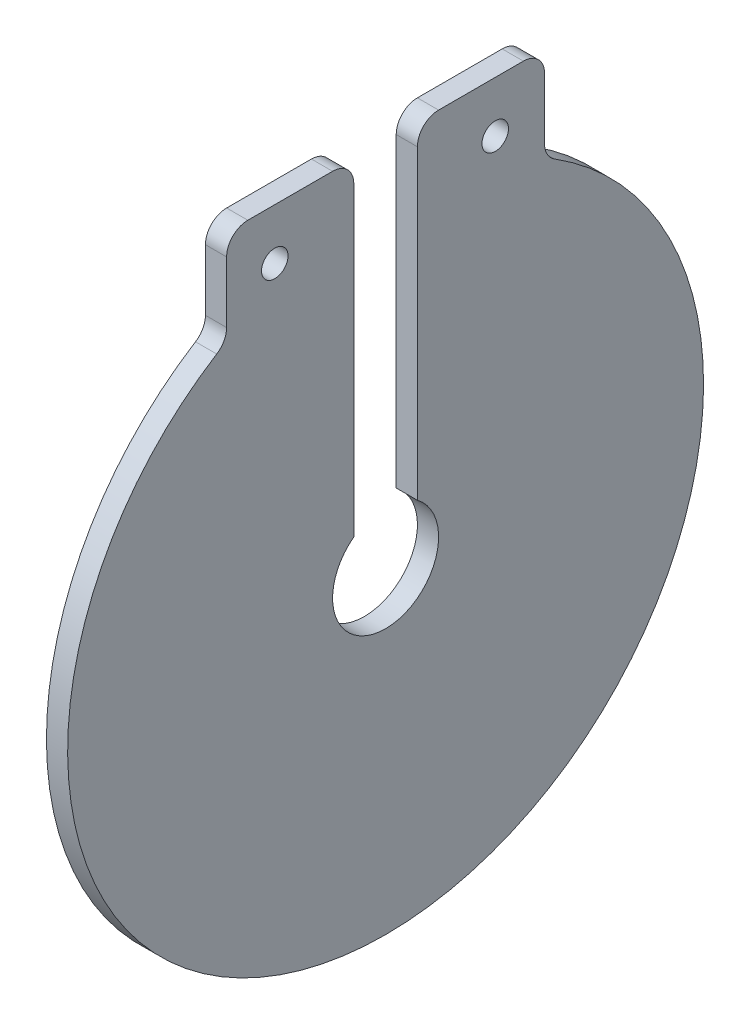
SolidWorks part; units mm, degrees
ref_plane "前视基准面" through (0, 0, 0) normal (0, 0, 1) x (1, 0, 0)
ref_plane "上视基准面" through (0, 0, 0) normal (0, 1, 0) x (1, 0, 0)
ref_plane "右视基准面" through (0, 0, 0) normal (1, 0, 0) x (0, 0, -1)
other "Configuration Table"
sketch "草图1" plane through (0, 0, 0) normal (1, 0, 0) x (0, 0, -1)
  circle A0 centre (0, 0) radius 30
  dimension "D1" = 60
extrude "凸台-拉伸1" add sketch "草图1" along normal blind 2
sketch "草图2" plane through (2, 0, 0) normal (1, 0, 0) x (0, 0, -1)
  line L0 (0, 30) -> (0, -30) construction
  circle A0 centre (0, 0) radius 30 construction
  circle A1 centre (0, 0) radius 5
  dimension "D1" = 10
extrude "切除-拉伸1" cut sketch "草图2" against normal blind 2 contours A1
sketch "草图5" plane through (2, 0, 0) normal (1, 0, 0) x (0, 0, -1)
  line L0 (0, 0) -> (0, 30.1572) construction
  line L2 (-15, 34.8808) -> (15, 34.8808)
  line L3 (-15, 34.8808) -> (-15, 25.9808)
  line L4 (-15, 25.9808) -> (15, 25.9808)
  line L5 (15, 34.8808) -> (15, 25.9808)
  circle A0 centre (0, 0) radius 30 construction
  point P7 (0, 0)
  point P8 (-15, 25.9808)
  dimension "D1" = 30
  dimension "D2" = 15
  dimension "D3" = 8.9
extrude "凸台-拉伸2" add sketch "草图5" against normal blind 2
sketch "草图4" plane through (2, 0, 0) normal (1, 0, 0) x (0, 0, -1)
  line L0 (0, 30) -> (0, 0) construction
  line L2 (-3, 38.3727) -> (3, 38.3727)
  line L3 (-3, 38.3727) -> (-3, 1.7509)
  line L4 (-3, 1.7509) -> (3, 1.7509)
  line L5 (3, 38.3727) -> (3, 1.7509)
  circle A0 centre (0, 0) radius 30 construction
  dimension "D1" = 6
  dimension "D2" = 3
extrude "切除-拉伸3" cut sketch "草图4" against normal blind 2
fillet "圆角1" radius 2 6 edges at (1, 34.8808, -15) (1, 34.8808, 15) (1, 25.9808, 15) (1, 25.9808, -15) (1, 34.8808, -3) (1, 34.8808, 3)
sketch "草图6" plane through (2, 0, 0) normal (1, 0, 0) x (0, 0, -1)
  line L0 (0, 0) -> (0, 34.7672) construction
  line L1 (-5, 34.8808) -> (-13, 34.8808) construction
  circle A0 centre (-10.4556, 30.0808) radius 1.25
  circle A1 centre (10.3444, 30.0808) radius 1.25
  point P9 (0, 0)
  point P10 (0, 0)
  point P11 (7.5089, 30.4105)
  dimension "D1" = 2.5
  dimension "D2" = 2.5
  dimension "D3" = 20.8
  dimension "D4" = 4.8
extrude "切除-拉伸4" cut sketch "草图6" against normal blind 2
